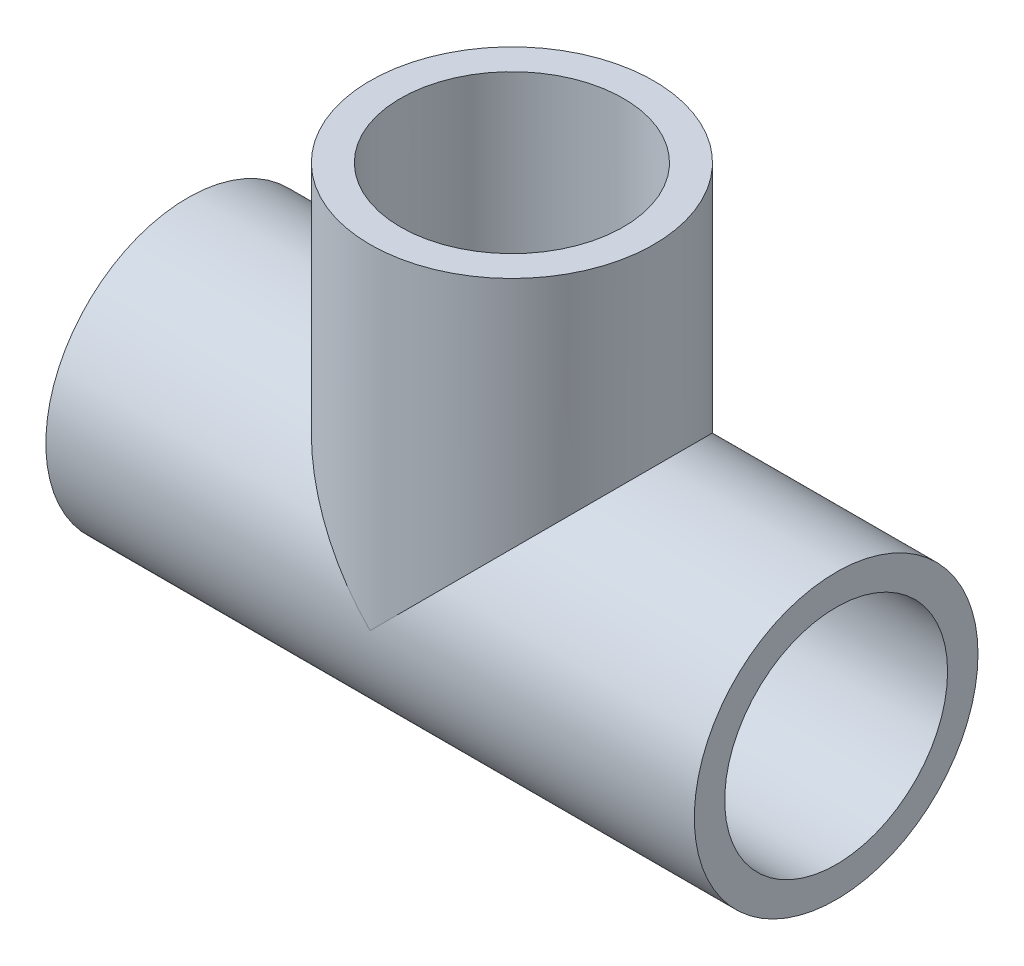
SolidWorks part; units mm, degrees
material "PVC 0.007 Plasticized"
ref_plane "Front Plane" through (0, 0, 0) normal (0, 0, 1) x (1, 0, 0)
ref_plane "Top Plane" through (0, 0, 0) normal (0, 1, 0) x (1, 0, 0)
ref_plane "Right Plane" through (0, 0, 0) normal (1, 0, 0) x (0, 0, -1)
sketch "Sketch1" plane through (0, 0, 0) normal (0, 0, 1) x (1, 0, 0)
  line L0 (32, 0) -> (-32, 0)
  point P5 (32, 0)
  point P6 (-32, 0)
ref_plane "Plane1" through (32, 0, 0) normal (1, 0, 0) x (0, 0, -1)
sketch "Sketch3" plane through (32, 0, 0) normal (1, 0, 0) x (0, 0, -1)
  circle A0 centre (0, 0) radius 14
  circle A1 centre (0, 0) radius 11
sweep "Sweep1" add profiles "Sketch3" path "Sketch1"
sketch "Sketch5" plane through (0, 0, 0) normal (0, 1, 0) x (1, 0, 0)
  circle A0 centre (0, 0) radius 14
  circle A1 centre (0, 0) radius 11
extrude "Boss-Extrude1" add sketch "Sketch5" along normal blind 33
sketch "Sketch6" plane through (-32, 0, 0) normal (-1, 0, 0) x (0, 0, 1)
  circle A0 centre (0, 0) radius 11
extrude "Cut-Extrude1" cut sketch "Sketch6" against normal blind 53
sketch "Sketch7" plane through (0, 33, 0) normal (0, 1, 0) x (1, 0, 0)
  circle A0 centre (0, 0) radius 11
extrude "Cut-Extrude2" cut sketch "Sketch7" against normal blind 33
